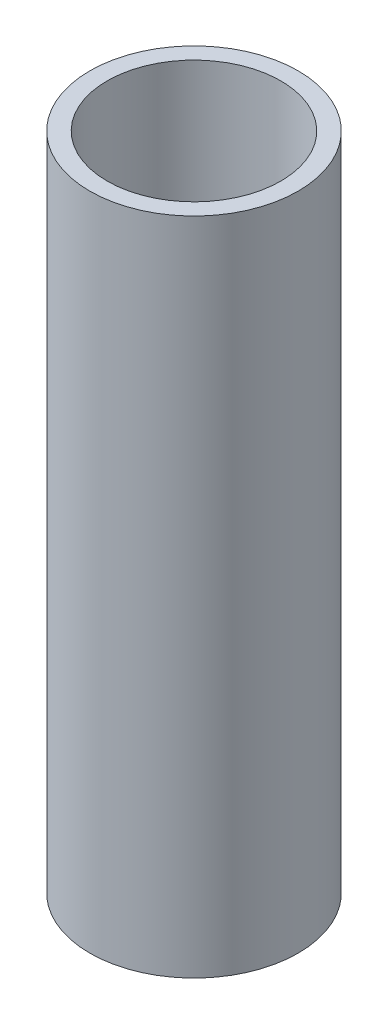
SolidWorks part; units mm, degrees
ref_plane "Front Plane" through (0, 0, 0) normal (0, 0, 1) x (1, 0, 0)
ref_plane "Top Plane" through (0, 0, 0) normal (0, 1, 0) x (1, 0, 0)
ref_plane "Right Plane" through (0, 0, 0) normal (1, 0, 0) x (0, 0, -1)
sketch "Эскиз1" plane through (0, 0, 0) normal (0, 1, 0) x (1, 0, 0)
  circle A0 centre (0, 0) radius 6
extrude "Бобышка-Вытянуть1" add sketch "Эскиз1" along normal blind 38
sketch "Эскиз2" plane through (0, 38, 0) normal (0, 1, 0) x (1, 0, 0)
  circle A0 centre (0, 0) radius 5
extrude "Вырез-Вытянуть1" cut sketch "Эскиз2" against normal through all
